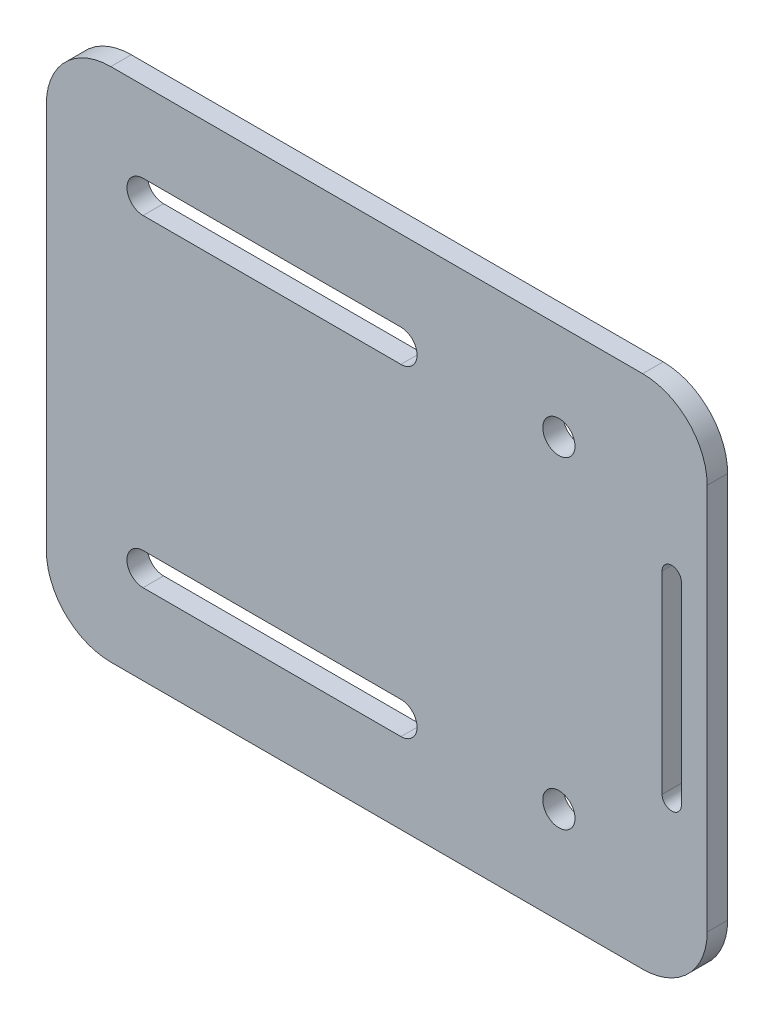
SolidWorks part; units mm, degrees
ref_plane "Front Plane" through (0, 0, 0) normal (0, 0, 1) x (1, 0, 0)
ref_plane "Top Plane" through (0, 0, 0) normal (0, 1, 0) x (1, 0, 0)
ref_plane "Right Plane" through (0, 0, 0) normal (1, 0, 0) x (0, 0, -1)
sketch "Sketch1" plane through (0, 0, 0) normal (0, 0, 1) x (1, 0, 0)
  line L0 (-64.5, 25) -> (-24.5, 25) construction
  line L1 (-79.5, -40) -> (23, -40)
  line L2 (-79.5, -40) -> (-79.5, 40)
  line L3 (-79.5, 40) -> (23, 40)
  line L4 (23, -40) -> (23, 40)
  line L5 (-64.5, -25) -> (-24.5, -25) construction
  line L6 (-64.5, -27.5) -> (-24.5, -27.5)
  line L9 (-64.5, -22.5) -> (-24.5, -22.5)
  line L11 (-64.5, 27.5) -> (-24.5, 27.5)
  line L14 (-64.5, 22.5) -> (-24.5, 22.5)
  line L20 (-79.5, 0) -> (40, 0) construction
  line L23 (17.5, 15) -> (17.5, -15) construction
  line L24 (19, 15) -> (19, -15)
  line L25 (16, 15) -> (16, -15)
  line L26 (-16, 40) -> (-16, -40) construction
  line L27 (0, 25) -> (0, -25) construction
  line L28 (16, 40) -> (16, -40) construction
  circle A12 centre (0, 25) radius 2.5
  circle A13 centre (0, -25) radius 2.5
  arc A22 (-64.5, 27.5) -> (-64.5, 22.5) centre (-64.5, 25) ccw
  arc A23 (-24.5, 22.5) -> (-24.5, 27.5) centre (-24.5, 25) ccw
  arc A26 (19, 15) -> (16, 15) centre (17.5, 15) ccw
  arc A27 (16, -15) -> (19, -15) centre (17.5, -15) ccw
  circle A28 centre (-24.5, 25) radius 8.5 construction
  arc A29 (-64.5, -27.5) -> (-64.5, -22.5) centre (-64.5, -25) cw
  arc A30 (-24.5, -22.5) -> (-24.5, -27.5) centre (-24.5, -25) cw
  point P0 (0, 0)
  point P6 (-44.5, 25)
  point P12 (17.5, 0)
  point P26 (-44.5, -25)
  dimension "D8" = 50
  dimension "D4" = 5
  dimension "D5" = 15
  dimension "D6" = 17
  dimension "D1" = 80
  dimension "D2" = 40
  dimension "D3" = 50
  dimension "D7" = 5
  dimension "D9" = 3
  dimension "D10" = 30
  dimension "D11" = 4
  dimension "D12" = 32
extrude "Boss-Extrude1" add sketch "Sketch1" along normal blind 3.175
fillet "Fillet1" radius 10 4 edges at (23, 40, 1.5875) (23, -40, 1.5875) (-79.5, -40, 1.5875) (-79.5, 40, 1.5875)
